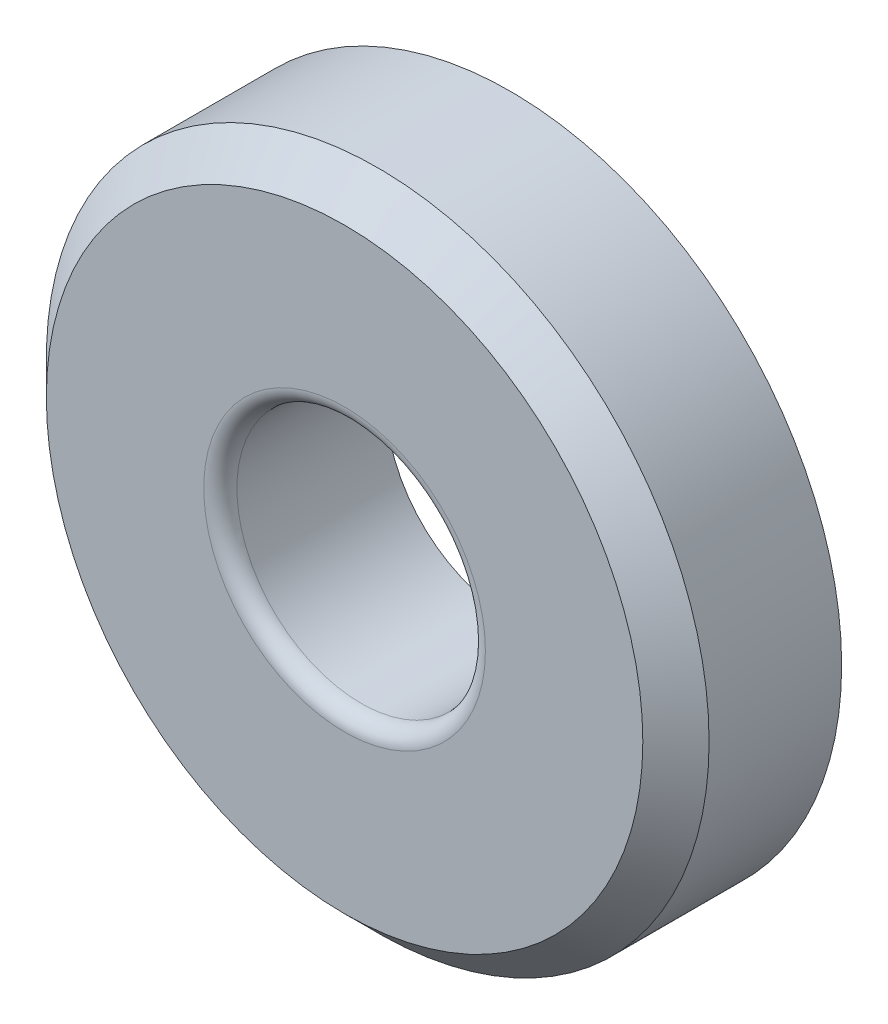
SolidWorks part; units mm, degrees
ref_plane "Front Plane" through (0, 0, 0) normal (0, 0, 1) x (1, 0, 0)
ref_plane "Top Plane" through (0, 0, 0) normal (0, 1, 0) x (1, 0, 0)
ref_plane "Right Plane" through (0, 0, 0) normal (1, 0, 0) x (0, 0, -1)
sketch "Sketch1" plane through (0, 0, 0) normal (0, 0, 1) x (1, 0, 0)
  circle A0 centre (0, 0) radius 9.525
  circle A1 centre (0, 0) radius 25.4
  dimension "D1" = 50.8
  dimension "D2" = 19.05
extrude "Boss-Extrude1" add sketch "Sketch1" along normal blind 12.7
chamfer "Chamfer1" distance 2.54 angle 45 1 edges at (25.4, 0, 12.7)
fillet "Fillet1" radius 1.27 1 edges at (9.525, 0, 12.7)
